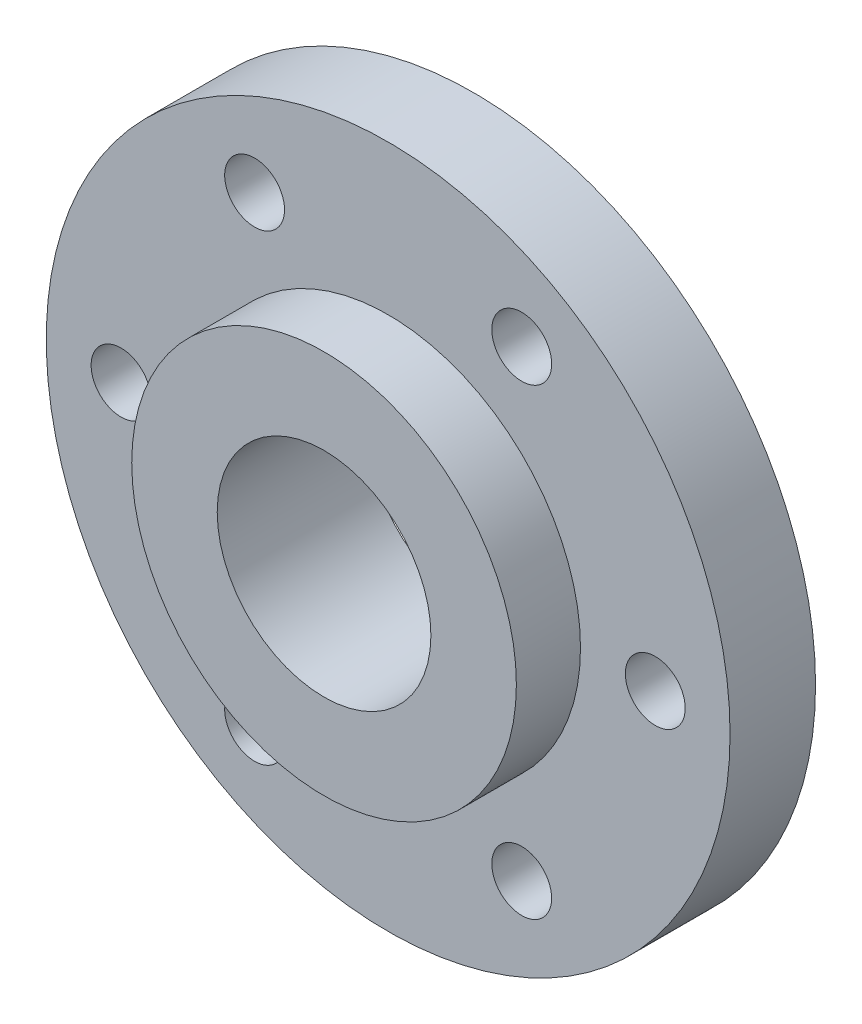
SolidWorks part; units mm, degrees
ref_plane "前视基准面" through (0, 0, 0) normal (0, 0, 1) x (1, 0, 0)
ref_plane "上视基准面" through (0, 0, 0) normal (0, 1, 0) x (1, 0, 0)
ref_plane "右视基准面" through (0, 0, 0) normal (1, 0, 0) x (0, 0, -1)
sketch "草图1" plane through (0, 0, 0) normal (0, 0, 1) x (1, 0, 0)
  circle A0 centre (0, 0) radius 80
  circle A1 centre (0, 0) radius 25
extrude "凸台-拉伸1" add sketch "草图1" against normal blind 20
sketch "草图2" plane through (0, 0, 0) normal (0, 0, 1) x (1, 0, 0)
  circle A0 centre (0, 0) radius 45
  circle A1 centre (0, 0) radius 25
extrude "凸台-拉伸2" add sketch "草图2" along normal blind 15
sketch "草图3" plane through (0, 0, 0) normal (0, 0, 1) x (1, 0, 0)
  circle A0 centre (62.5, 0) radius 7
  circle A1 centre (31.25, 54.1266) radius 7
  circle A2 centre (-31.25, 54.1266) radius 7
  circle A3 centre (-62.5, 0) radius 7
  circle A4 centre (-31.25, -54.1266) radius 7
  circle A5 centre (31.25, -54.1266) radius 7
extrude "切除-拉伸1" cut sketch "草图3" along normal through all and the other way through all
